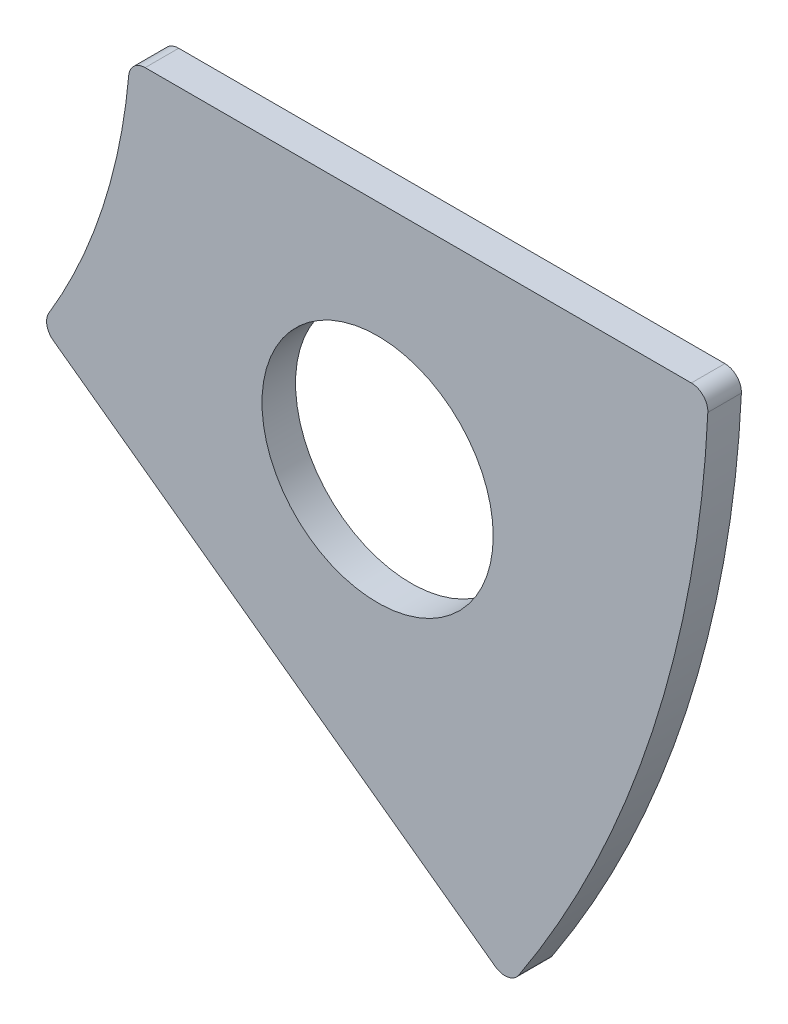
SolidWorks part; units mm, degrees
material "Copper"
ref_plane "Front Plane" through (0, 0, 0) normal (0, 0, 1) x (1, 0, 0)
ref_plane "Top Plane" through (0, 0, 0) normal (0, 1, 0) x (1, 0, 0)
ref_plane "Right Plane" through (0, 0, 0) normal (1, 0, 0) x (0, 0, -1)
sketch "Sketch1" plane through (0, 0, 0) normal (0, 0, 1) x (1, 0, 0)
  line L0 (0, 0) -> (67.1445, 0) construction
  line L1 (0, 0) -> (53.4847, -38.8589) construction
  line L2 (17.4654, -1.1) -> (34.9827, -1.1)
  line L3 (14.7764, -9.376) -> (28.9482, -19.6724)
  arc A0 (14.7764, -9.376) -> (17.4654, -1.1) centre (0, 0) ccw
  arc A1 (28.9482, -19.6724) -> (34.9827, -1.1) centre (0, 0) ccw
  dimension "D4" = 17.5
  dimension "D5" = 35
  dimension "D1" = 36
  dimension "D2" = 1.1
  dimension "D3" = 1.1
extrude "Boss-Extrude1" add sketch "Sketch1" along normal blind 1.016
hole_wizard "M6 Clearance Hole1" positions "Sketch2" profile "Sketch3" hole size "M6" standard "ANSI Metric" end condition up to next
sketch "Sketch2" plane through (0, 0, 1.016) normal (0, 0, 1) x (1, 0, 0)
  line L0 (0, 0) -> (46.5591, 0) construction
  line L2 (0, 0) -> (44.6079, -14.494) construction
  point P0 (24.9652, -8.1117)
  dimension "D1" = 18
  dimension "D2" = 26.25
sketch "Sketch3" plane through (24.9652, -8.1117, 1.016) normal (1, 0, 0) x (0, -1, 0)
  line L0 (0, 0) -> (0, 1.016)
  line L1 (0, 1.016) -> (3.5, 1.016)
  line L2 (3.5, 1.016) -> (3.5, 0)
  line L5 (3.5, 0) -> (0, 0)
  line L11 (0, -6.35) -> (0, 107.95) construction
  dimension "Thru Hole Dia." = 7
  dimension "Thru Hole Depth" = 1.016
sketch "Sketch4" plane through (0, 0, 1.016) normal (0, 0, 1) x (1, 0, 0)
  line L0 (0, 0) -> (40.157, 0) construction
  line L1 (0, 0) -> (33.9066, -24.6346) construction
  circle A0 centre (28.3156, -20.5725) radius 1.1
  circle A1 centre (14.1578, -10.2862) radius 1.1
  circle A2 centre (17.5, 0) radius 1.1
  circle A3 centre (35, 0) radius 1.1
  dimension "D1" = 2.2
  dimension "D2" = 2.2
  dimension "D3" = 2.2
  dimension "D4" = 2.2
  dimension "D5" = 36
  dimension "D6" = 17.5
  dimension "D7" = 17.5
  dimension "D8" = 35
  dimension "D9" = 35
fillet "Fillet2" radius 0.5 4 edges at (14.7764, -9.376, 0.508) (17.4654, -1.1, 0.508) (34.9827, -1.1, 0.508) (28.9482, -19.6724, 0.508)
sketch "Sketch5" [suppressed] plane through (0, 0, 6.35) normal (0, 0, 1) x (1, 0, 0)
  circle A0 centre (24.9652, -8.1117) radius 4.5
extrude "Cut-Extrude1" [suppressed] cut sketch "Sketch5" against normal blind 0.65
sketch "Sketch6" [suppressed] plane through (0, 0, 0) normal (0, 0, -1) x (-1, 0, 0)
  circle A0 centre (-24.9652, -8.1117) radius 4.5
extrude "Cut-Extrude2" [suppressed] cut sketch "Sketch6" against normal blind 0.65
